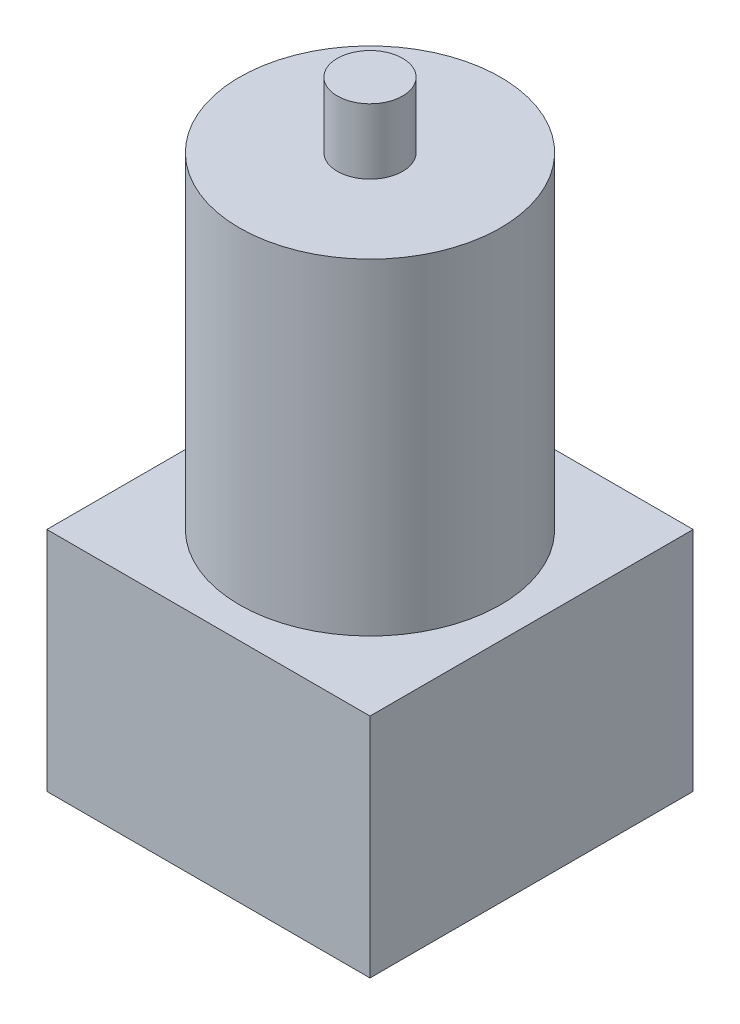
SolidWorks part; units mm, degrees
ref_plane "Front Plane" through (0, 0, 0) normal (0, 0, 1) x (1, 0, 0)
ref_plane "Top Plane" through (0, 0, 0) normal (0, 1, 0) x (1, 0, 0)
ref_plane "Right Plane" through (0, 0, 0) normal (1, 0, 0) x (0, 0, -1)
sketch "Sketch1" plane through (0, 0, 0) normal (0, 1, 0) x (1, 0, 0)
  circle A0 centre (0, 0) radius 20
  dimension "D1" = 40
extrude "Boss-Extrude1" add sketch "Sketch1" along normal blind 50
sketch "Sketch2" plane through (0, 50, 0) normal (0, 1, 0) x (1, 0, 0)
  circle A0 centre (0, 0) radius 5
  dimension "D1" = 10
extrude "Boss-Extrude2" add sketch "Sketch2" along normal blind 10
sketch "Sketch3" plane through (0, 0, 0) normal (0, 0, 1) x (1, 0, 0)
  line L0 (0, 0) -> (0, 68.5672) construction
  circle A0 centre (0, 55.8365) radius 1.5
  dimension "D1" = 3
extrude "Cut-Extrude1" cut sketch "Sketch3" against normal blind 16
ref_plane "Plane1" through (0, 0, 0) normal (0, -1, 0) x (-1, 0, 0)
sketch "Sketch4" plane through (0, 0, 0) normal (0, -1, 0) x (-1, 0, 0)
  line L1 (24.75, -24.75) -> (-24.75, -24.75)
  line L2 (24.75, -24.75) -> (24.75, 24.75)
  line L3 (24.75, 24.75) -> (-24.75, 24.75)
  line L4 (-24.75, -24.75) -> (-24.75, 24.75)
  line L5 (24.75, -24.75) -> (-24.75, 24.75) construction
  line L6 (24.75, 24.75) -> (-24.75, -24.75) construction
  point P0 (0, 0)
  dimension "D1" = 49.5
  dimension "D2" = 49.5
extrude "Boss-Extrude3" add sketch "Sketch4" along normal blind 34.75
